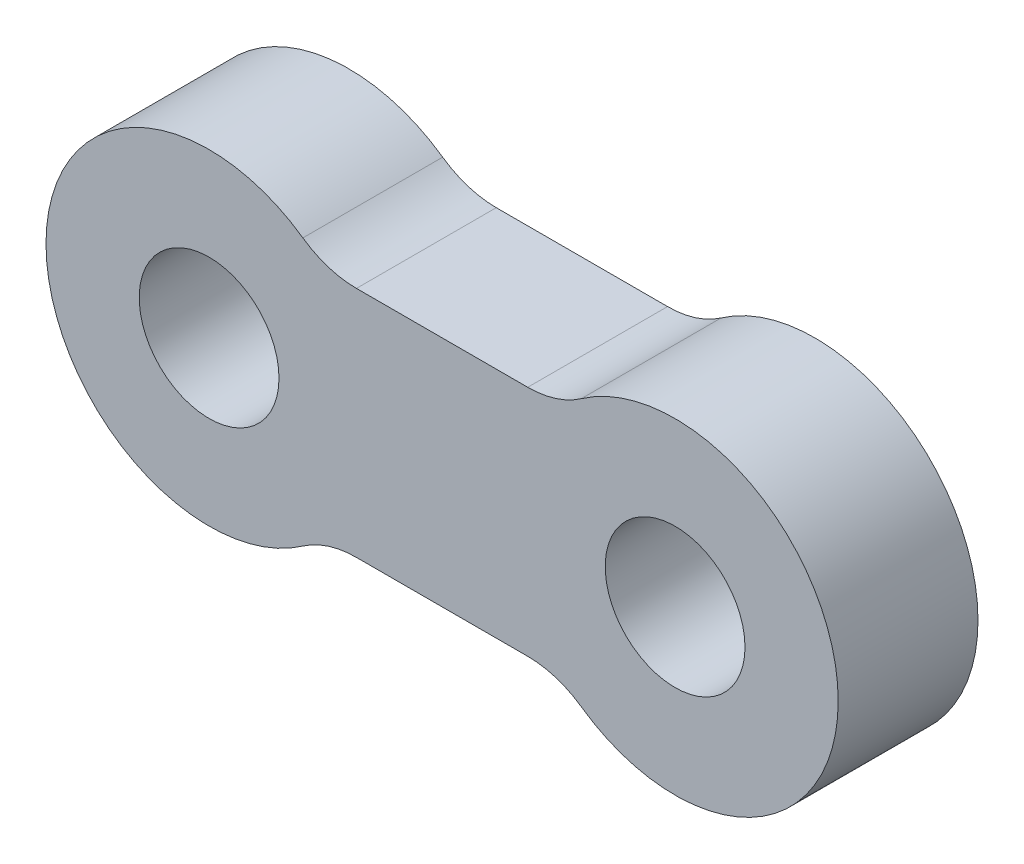
SolidWorks part; units mm, degrees
ref_plane "前视基准面" through (0, 0, 0) normal (0, 0, 1) x (1, 0, 0)
ref_plane "上视基准面" through (0, 0, 0) normal (0, 1, 0) x (1, 0, 0)
ref_plane "右视基准面" through (0, 0, 0) normal (1, 0, 0) x (0, 0, -1)
sketch "草图1" plane through (0, 0, 0) normal (0, 0, 1) x (1, 0, 0)
  line L0 (-11.7237, 0) -> (31.9737, 0) construction
  line L1 (5, 3.902) -> (5, -4.7147) construction
  line L2 (3.1623, 2.5) -> (6.8377, 2.5)
  line L3 (3.1623, -2.5) -> (6.8377, -2.5)
  circle A0 centre (0, 0) radius 1.5
  circle A1 centre (10, 0) radius 1.5
  arc A2 (2.0124, 2.8636) -> (2.0124, -2.8636) centre (0, 0) ccw
  arc A3 (7.9876, 2.8636) -> (7.9876, -2.8636) centre (10, 0) cw
  arc A4 (6.8377, -2.5) -> (7.9876, -2.8636) centre (6.8377, -4.5) cw
  arc A5 (3.1623, -2.5) -> (2.0124, -2.8636) centre (3.1623, -4.5) ccw
  arc A6 (7.9876, 2.8636) -> (6.8377, 2.5) centre (6.8377, 4.5) cw
  arc A7 (3.1623, 2.5) -> (2.0124, 2.8636) centre (3.1623, 4.5) cw
  point P17 (7.5505, -2.5)
  point P20 (2.4495, -2.5)
  point P23 (7.5505, 2.5)
  point P26 (2.4495, 2.5)
  dimension "D1" = 3
  dimension "D2" = 10
  dimension "D3" = 7
  dimension "D4" = 2
  dimension "D5" = 5
extrude "凸台-拉伸1" add sketch "草图1" along normal blind 3
